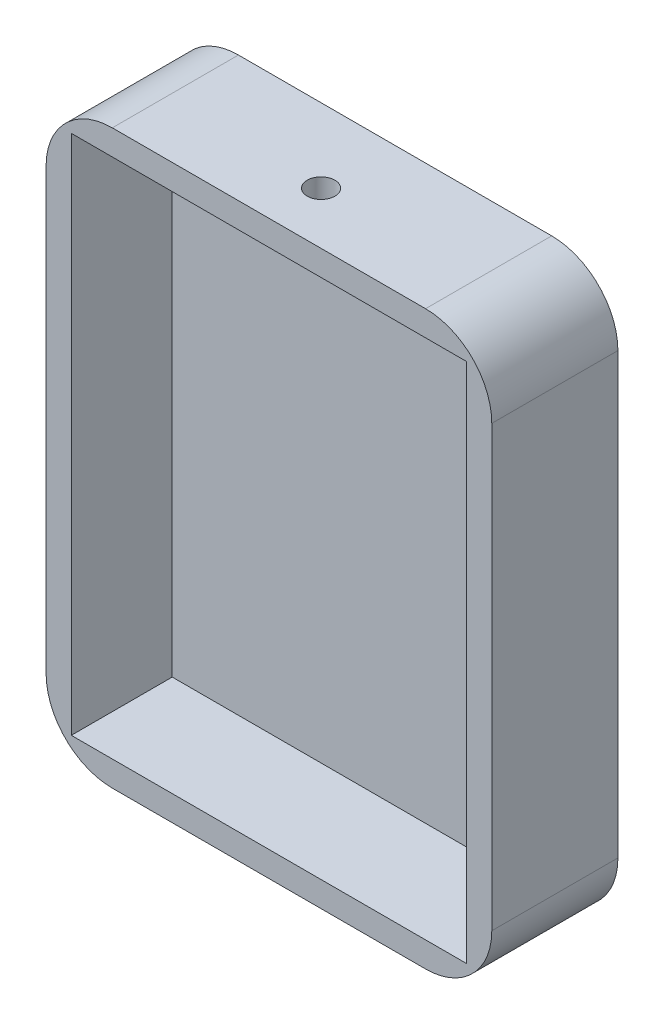
SolidWorks part; units mm, degrees
ref_plane "Front Plane" through (0, 0, 0) normal (0, 0, 1) x (1, 0, 0)
ref_plane "Top Plane" through (0, 0, 0) normal (0, 1, 0) x (1, 0, 0)
ref_plane "Right Plane" through (0, 0, 0) normal (1, 0, 0) x (0, 0, -1)
sketch "Sketch1" plane through (0, 0, 0) normal (0, 0, 1) x (1, 0, 0)
  line L1 (-33.655, -43.18) -> (33.655, -43.18)
  line L2 (-33.655, -43.18) -> (-33.655, 43.18)
  line L3 (-33.655, 43.18) -> (33.655, 43.18)
  line L4 (33.655, -43.18) -> (33.655, 43.18)
  line L5 (-33.655, -43.18) -> (33.655, 43.18) construction
  line L6 (-33.655, 43.18) -> (33.655, -43.18) construction
  point P0 (0, 0)
  dimension "D1" = 67.31
  dimension "D2" = 86.36
extrude "Boss-Extrude1" add sketch "Sketch1" along normal blind 19.05
shell "Shell1" thickness 3.81
fillet "Fillet3" radius 10 4 edges at (-33.655, -43.18, 9.525) (-33.655, 43.18, 9.525) (33.655, -43.18, 9.525) (33.655, 43.18, 9.525)
sketch "Sketch2" plane through (0, 43.18, 0) normal (0, 1, 0) x (1, 0, 0)
  line L0 (23.655, 0) -> (-23.655, 0) construction
  circle A0 centre (0, -11.176) radius 2.0955
  dimension "D1" = 4.191
  dimension "D2" = 11.176
extrude "Cut-Extrude1" cut sketch "Sketch2" against normal up to next
